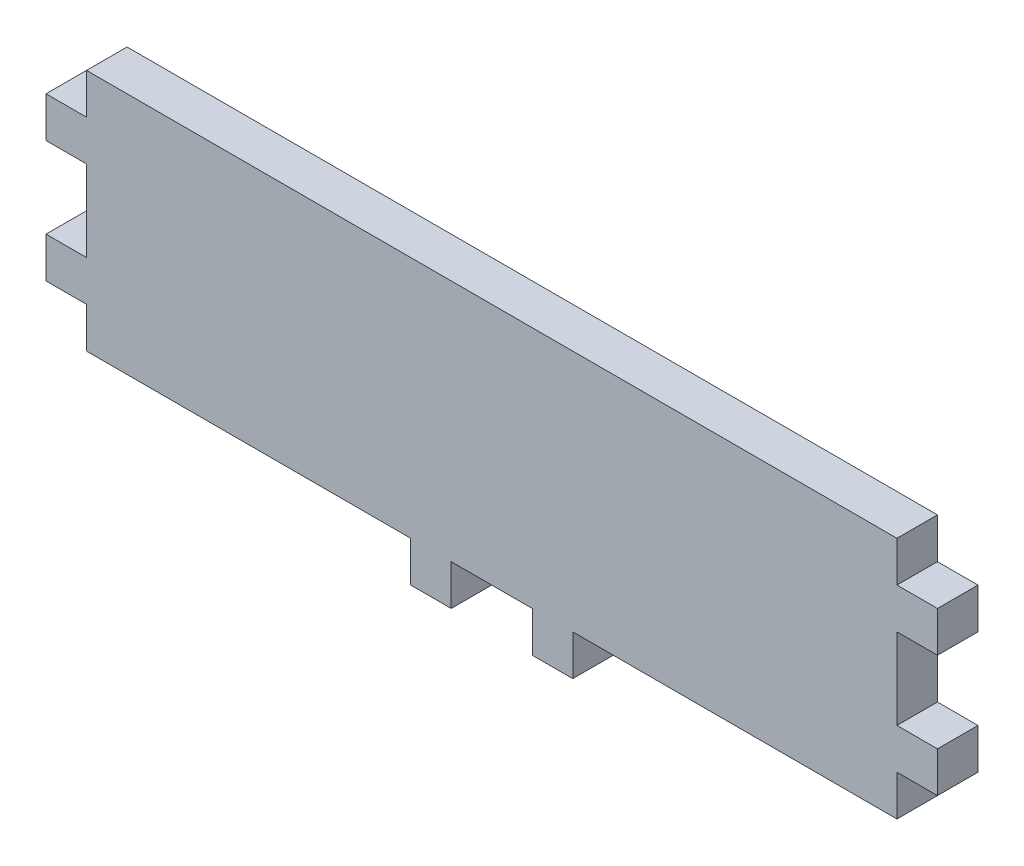
SolidWorks part; units mm, degrees
ref_plane "Front Plane" through (0, 0, 0) normal (0, 0, 1) x (1, 0, 0)
ref_plane "Top Plane" through (0, 0, 0) normal (0, 1, 0) x (1, 0, 0)
ref_plane "Right Plane" through (0, 0, 0) normal (1, 0, 0) x (0, 0, -1)
sketch "Sketch1" plane through (0, 0, 0) normal (0, 0, 1) x (1, 0, 0)
  line L0 (0, 0) -> (0, 5)
  line L1 (0, 5) -> (-40, 5)
  line L2 (-40, 5) -> (-40, 10.0003)
  line L3 (-40, 10.0003) -> (-45, 10.0003)
  line L4 (-45, 10.0003) -> (-45, 15.0003)
  line L5 (-45, 15.0003) -> (-40, 15.0003)
  line L6 (-40, 15.0003) -> (-40, 25.0003)
  line L7 (-40, 25.0003) -> (-45, 25.0003)
  line L8 (-45, 25.0003) -> (-45, 30.0003)
  line L9 (-45, 30.0003) -> (-40, 30.0003)
  line L10 (-40, 30.0003) -> (-40, 35)
  line L11 (-40, 35) -> (60, 35)
  line L12 (60, 35) -> (60, 30.0003)
  line L13 (60, 30.0003) -> (65, 30.0003)
  line L14 (65, 30.0003) -> (65, 25.0003)
  line L15 (65, 25.0003) -> (60, 25.0003)
  line L16 (60, 25.0003) -> (60, 15.0003)
  line L17 (60, 15.0003) -> (65, 15.0003)
  line L18 (65, 15.0003) -> (65, 10.0003)
  line L19 (65, 10.0003) -> (60, 10.0003)
  line L20 (60, 10.0003) -> (60, 5)
  line L21 (60, 5) -> (20, 5)
  line L22 (20, 5) -> (20, 0)
  line L23 (20, 0) -> (15, 0)
  line L24 (15, 0) -> (15, 5)
  line L25 (15, 5) -> (5, 5)
  line L26 (5, 5) -> (5, 0)
  line L27 (5, 0) -> (0, 0)
  line L28 (10, 38.8616) -> (10, -3.1032) construction
  point P31 (10, 35)
  dimension "D1" = 5
  dimension "D2" = 10
  dimension "D3" = 5
  dimension "D4" = 10
  dimension "D5" = 100
  dimension "D6" = 30
extrude "Boss-Extrude1" add sketch "Sketch1" along normal blind 5
